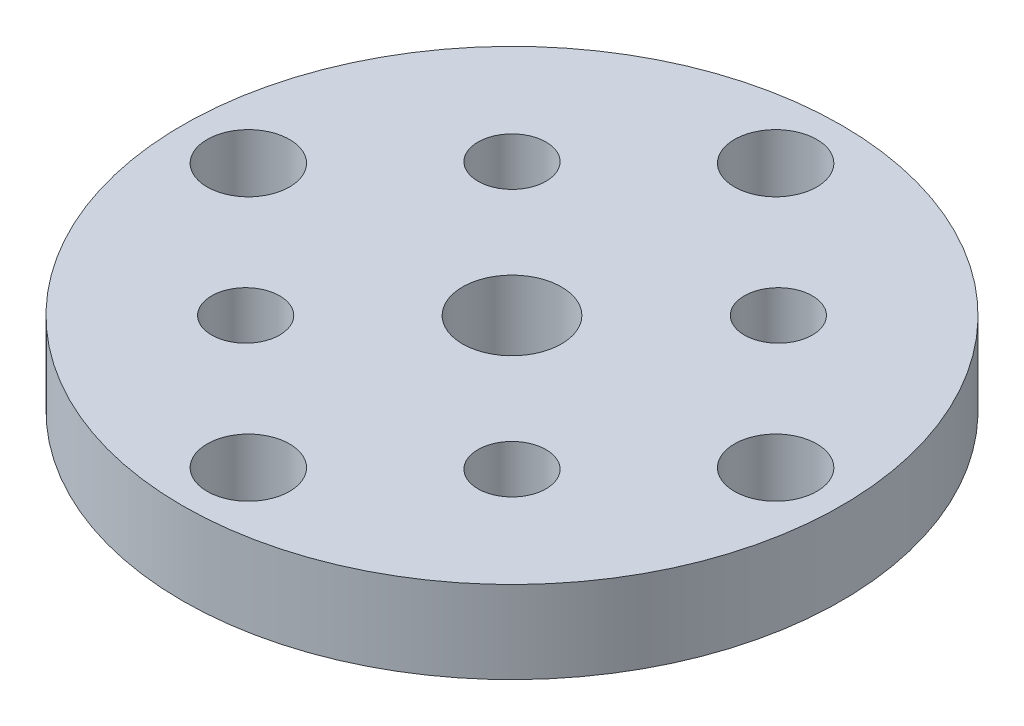
SolidWorks part; units mm, degrees
material "2014-T6"
ref_plane "Front Plane" through (0, 0, 0) normal (0, 0, 1) x (1, 0, 0)
ref_plane "Top Plane" through (0, 0, 0) normal (0, 1, 0) x (1, 0, 0)
ref_plane "Right Plane" through (0, 0, 0) normal (1, 0, 0) x (0, 0, -1)
sketch "Sketch1" plane through (0, 0, 0) normal (0, 1, 0) x (1, 0, 0)
  line L0 (0, 24.1217) -> (0, -25.5168) construction
  line L1 (-33.1168, 0) -> (38.4772, 0) construction
  circle A0 centre (0, 0) radius 10
  circle A1 centre (0, 0) radius 1.5
  circle A2 centre (0, 8) radius 1.25
  circle A3 centre (0, 0) radius 10
  circle A4 centre (8, 0) radius 1.25
  circle A5 centre (0, 0) radius 10
  circle A6 centre (0, -8) radius 1.25
  circle A7 centre (0, 0) radius 10
  circle A8 centre (-8, 0) radius 1.25
  point P22 (0, 0)
  dimension "D1" = 20
  dimension "D2" = 3
  dimension "D3" = 2.5
  dimension "D5" = 8
  dimension "D4" = 4
extrude "Boss-Extrude1" add sketch "Sketch1" along normal blind 2.5 contours A0 A8 A6 A4 A2 A1
cosmetic thread "Cosmetic Thread1" parameters "D1"=2.4999, "D2"=3
cosmetic thread "Cosmetic Thread2" parameters "D1"=2.4999, "D2"=3
cosmetic thread "Cosmetic Thread3" parameters "D1"=2.4999, "D2"=3
cosmetic thread "Cosmetic Thread4" parameters "D1"=2.4999, "D2"=3
sketch "Sketch2" plane through (0, 2.5, 0) normal (0, 1, 0) x (1, 0, 0)
  line L0 (-10.1496, 10.1496) -> (11.2798, -11.2798) construction
  line L1 (10.8654, 10.8654) -> (-10.8654, -10.8654) construction
  line L2 (0, 10.6288) -> (0, -11.3901) construction
  circle A0 centre (0, 0) radius 5.715 construction
  circle A1 centre (-4.0411, 4.0411) radius 1.0325
  circle A2 centre (4.0411, 4.0411) radius 1.0325
  circle A3 centre (4.0411, -4.0411) radius 1.0325
  circle A4 centre (-4.0411, -4.0411) radius 1.0325
  dimension "D1" = 11.43
  dimension "D3" = 2.065
  dimension "D2" = 45
extrude "Cut-Extrude1" cut sketch "Sketch2" against normal through all
